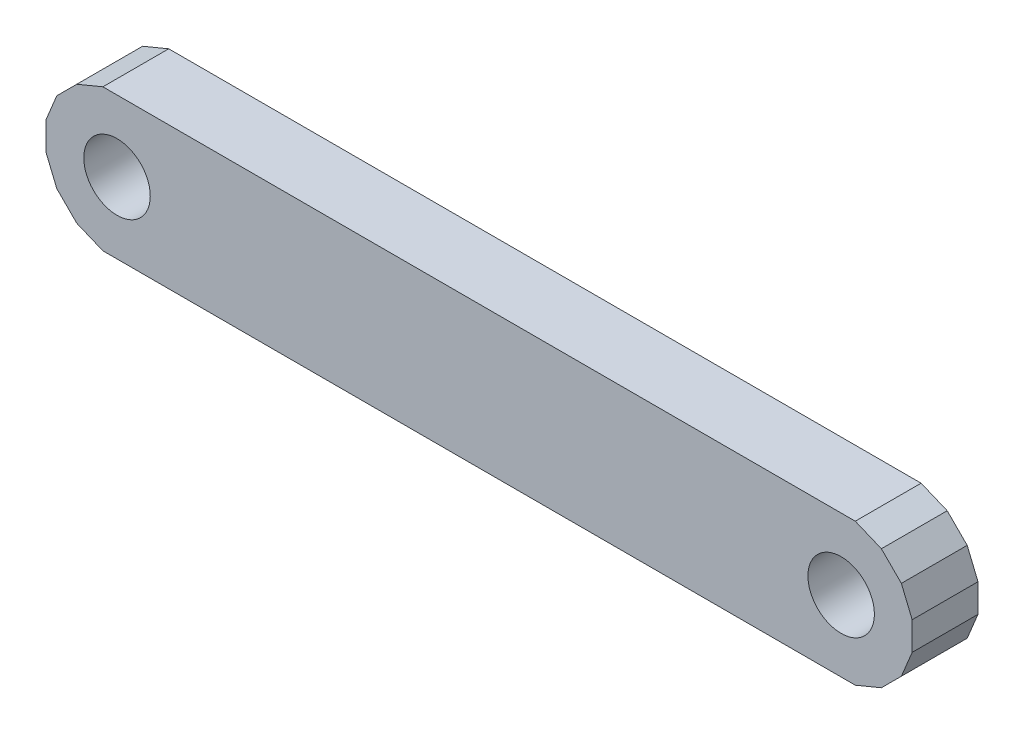
SolidWorks part; units mm, degrees
ref_plane "前视基准面" through (0, 0, 0) normal (0, 0, 1) x (1, 0, 0)
ref_plane "上视基准面" through (0, 0, 0) normal (0, 1, 0) x (1, 0, 0)
ref_plane "右视基准面" through (0, 0, 0) normal (1, 0, 0) x (0, 0, -1)
other "Configuration Table"
sketch "Profile_1" plane through (0, 0, 0) normal (0, 0, 1) x (1, 0, 0)
  line L0 (-10.7886, 2.146) -> (-10.7886, -2.146)
  line L1 (-10.7886, -2.146) -> (-9.1462, -6.1113)
  line L2 (-9.1462, -6.1113) -> (-6.1113, -9.1462)
  line L3 (-6.1113, -9.1462) -> (-2.146, -10.7886)
  line L4 (-2.146, -10.7886) -> (112.146, -10.7886)
  line L5 (112.146, -10.7886) -> (116.1113, -9.1462)
  line L6 (116.1113, -9.1462) -> (119.1462, -6.1113)
  line L7 (119.1462, -6.1113) -> (120.7886, -2.146)
  line L8 (120.7886, -2.146) -> (120.7886, 2.146)
  line L9 (120.7886, 2.146) -> (119.1462, 6.1113)
  line L10 (119.1462, 6.1113) -> (116.1113, 9.1462)
  line L11 (116.1113, 9.1462) -> (112.146, 10.7886)
  line L12 (112.146, 10.7886) -> (-2.146, 10.7886)
  line L13 (-2.146, 10.7886) -> (-6.1113, 9.1462)
  line L14 (-6.1113, 9.1462) -> (-9.1462, 6.1113)
  line L15 (-9.1462, 6.1113) -> (-10.7886, 2.146)
  circle A0 centre (0, 0) radius 5.05
  circle A1 centre (110, 0) radius 5.05
extrude "Passive_arm" add sketch "Profile_1" along normal blind 10 from offset 8
